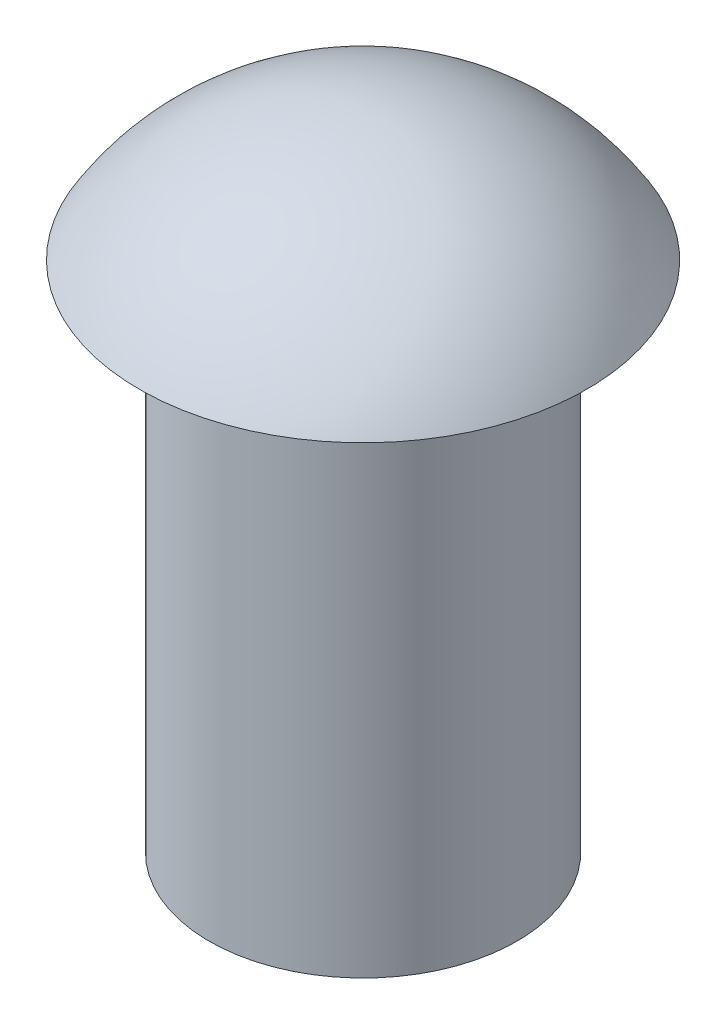
SolidWorks part; units mm, degrees
ref_plane "Front Plane" through (0, 0, 0) normal (0, 0, 1) x (1, 0, 0)
ref_plane "Top Plane" through (0, 0, 0) normal (0, 1, 0) x (1, 0, 0)
ref_plane "Right Plane" through (0, 0, 0) normal (1, 0, 0) x (0, 0, -1)
sketch "Sketch1" plane through (0, 0, 0) normal (0, 0, 1) x (1, 0, 0)
  line L0 (0, 6.8578) -> (0, 0)
  line L1 (0, 0) -> (-1.65, 0)
  line L2 (-1.65, 0) -> (-1.65, 5.5)
  line L3 (-1.65, 5.5) -> (-2.4, 5.5)
  arc A1 (-2.4, 5.5) -> (0, 6.8578) centre (0, 4.0578) cw
  point P1 (0, 0)
  point P5 (2.5992, -0.6197)
  point P9 (0, 0)
  point P10 (0, 0)
  point P11 (0, -0.4679)
  point P12 (0, 6.165)
  point P13 (0, 0)
  point P14 (0, 2.3898)
  point P15 (0, 5.1934)
  dimension "D3" = 2.8
  dimension "D1" = 1.65
  dimension "D2" = 5.5
  dimension "D4" = 0.75
revolve "Revolve1" add sketch "Sketch1" angle 360 about L0
